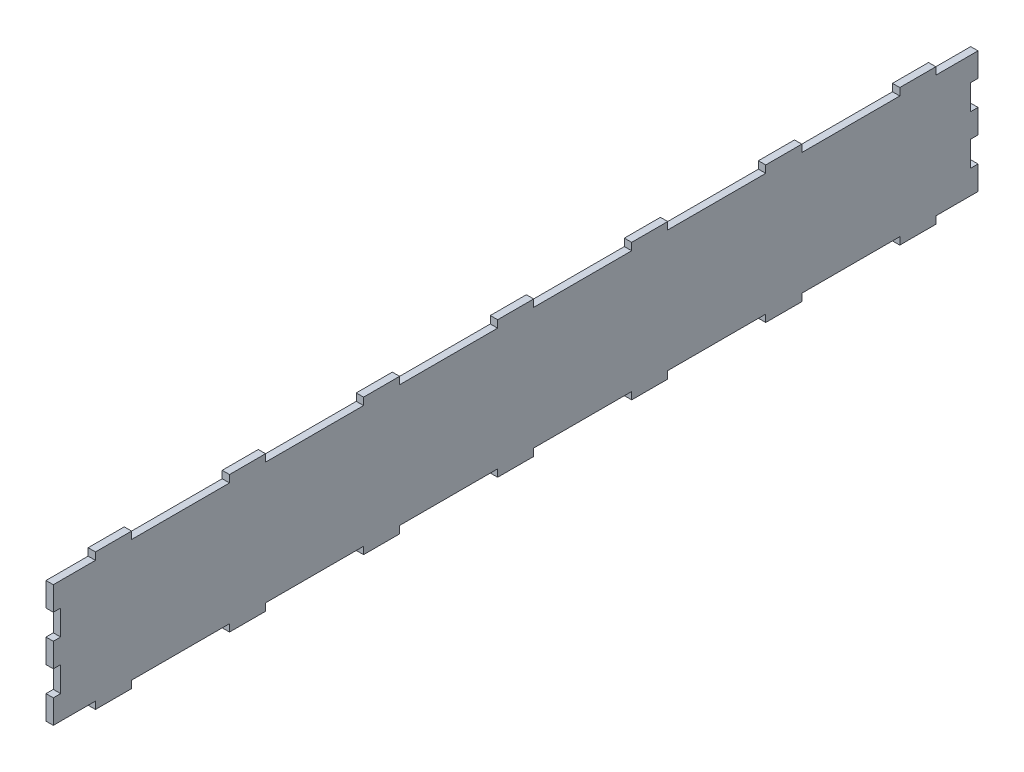
SolidWorks part; units mm, degrees
ref_plane "Front Plane" through (0, 0, 0) normal (0, 0, 1) x (1, 0, 0)
ref_plane "Top Plane" through (0, 0, 0) normal (0, 1, 0) x (1, 0, 0)
ref_plane "Right Plane" through (0, 0, 0) normal (1, 0, 0) x (0, 0, -1)
sketch "Sketch1" plane through (0, 0, 0) normal (1, 0, 0) x (0, 0, -1)
  line L0 (7.4, 0) -> (-7.4, 0)
  line L1 (7.4, 0) -> (7.4, -3)
  line L2 (7.4, -3) -> (47.6, -3)
  line L3 (47.6, -3) -> (47.6, 0)
  line L4 (47.6, 0) -> (62.4, 0)
  line L5 (62.4, 0) -> (62.4, -3)
  line L6 (62.4, -3) -> (102.6, -3)
  line L7 (102.6, -3) -> (102.6, 0)
  line L8 (102.6, 0) -> (117.4, 0)
  line L9 (117.4, 0) -> (117.4, -3)
  line L10 (117.4, -3) -> (157.6, -3)
  line L11 (157.6, -3) -> (157.6, 0)
  line L12 (157.6, 0) -> (172.4, 0)
  line L13 (172.4, 0) -> (172.4, -3)
  line L14 (172.4, -3) -> (189.7, -3)
  line L15 (189.7, -3) -> (189.7, -12.8)
  line L16 (189.7, -12.8) -> (186.7, -12.8)
  line L17 (186.7, -12.8) -> (186.7, -23.1)
  line L18 (186.7, -23.1) -> (189.7, -23.1)
  line L19 (189.7, -23.1) -> (189.7, -28)
  line L20 (0, 0) -> (0, -56) construction
  line L21 (-189.7, -28) -> (189.7, -28) construction
  line L22 (186.7, -43.2) -> (186.7, -32.9)
  line L23 (189.7, -43.2) -> (186.7, -43.2)
  line L24 (189.7, -53) -> (189.7, -43.2)
  line L25 (172.4, -53) -> (189.7, -53)
  line L26 (172.4, -56) -> (172.4, -53)
  line L27 (157.6, -56) -> (172.4, -56)
  line L28 (157.6, -53) -> (157.6, -56)
  line L29 (117.4, -53) -> (157.6, -53)
  line L30 (117.4, -56) -> (117.4, -53)
  line L31 (102.6, -56) -> (117.4, -56)
  line L32 (102.6, -53) -> (102.6, -56)
  line L33 (62.4, -53) -> (102.6, -53)
  line L34 (62.4, -56) -> (62.4, -53)
  line L35 (47.6, -56) -> (62.4, -56)
  line L36 (47.6, -53) -> (47.6, -56)
  line L37 (7.4, -53) -> (47.6, -53)
  line L38 (7.4, -56) -> (7.4, -53)
  line L39 (7.4, -56) -> (-7.4, -56)
  line L40 (-7.4, -56) -> (-7.4, -53)
  line L41 (-7.4, -53) -> (-47.6, -53)
  line L42 (-47.6, -53) -> (-47.6, -56)
  line L43 (-47.6, -56) -> (-62.4, -56)
  line L44 (-62.4, -56) -> (-62.4, -53)
  line L45 (-62.4, -53) -> (-102.6, -53)
  line L46 (-102.6, -53) -> (-102.6, -56)
  line L47 (-102.6, -56) -> (-117.4, -56)
  line L48 (-117.4, -56) -> (-117.4, -53)
  line L49 (-117.4, -53) -> (-157.6, -53)
  line L50 (-157.6, -53) -> (-157.6, -56)
  line L51 (-157.6, -56) -> (-172.4, -56)
  line L52 (-172.4, -56) -> (-172.4, -53)
  line L53 (-172.4, -53) -> (-189.7, -53)
  line L54 (-189.7, -53) -> (-189.7, -43.2)
  line L55 (-189.7, -43.2) -> (-186.7, -43.2)
  line L56 (-186.7, -43.2) -> (-186.7, -32.9)
  line L57 (-189.7, -23.1) -> (-189.7, -28)
  line L58 (-186.7, -23.1) -> (-189.7, -23.1)
  line L59 (-186.7, -12.8) -> (-186.7, -23.1)
  line L60 (-189.7, -12.8) -> (-186.7, -12.8)
  line L61 (-189.7, -3) -> (-189.7, -12.8)
  line L62 (-172.4, -3) -> (-189.7, -3)
  line L63 (-172.4, 0) -> (-172.4, -3)
  line L64 (-157.6, 0) -> (-172.4, 0)
  line L65 (-157.6, -3) -> (-157.6, 0)
  line L66 (-117.4, -3) -> (-157.6, -3)
  line L67 (-117.4, 0) -> (-117.4, -3)
  line L68 (-102.6, 0) -> (-117.4, 0)
  line L69 (-102.6, -3) -> (-102.6, 0)
  line L70 (-62.4, -3) -> (-102.6, -3)
  line L71 (-62.4, 0) -> (-62.4, -3)
  line L72 (-47.6, 0) -> (-62.4, 0)
  line L73 (-47.6, -3) -> (-47.6, 0)
  line L74 (-7.4, -3) -> (-47.6, -3)
  line L75 (-7.4, 0) -> (-7.4, -3)
  line L76 (186.7, -32.9) -> (189.7, -32.9)
  line L77 (189.7, -32.9) -> (189.7, -28)
  line L78 (-189.7, -28) -> (-189.7, -32.9)
  line L79 (-189.7, -32.9) -> (-186.7, -32.9)
  point P43 (0, -28)
  dimension "D1" = 14.8
  dimension "D2" = 3
  dimension "D3" = 7.4
  dimension "D4" = 40.2
  dimension "D5" = 9.8
  dimension "D6" = 10.3
  dimension "D7" = 4.9
  dimension "D8" = 3
  dimension "D9" = 3
  dimension "D10" = 28
  dimension "D11" = 17.3
  dimension "D12" = 14.8
  dimension "D13" = 14.8
extrude "Boss-Extrude1" add sketch "Sketch1" along normal blind 3
